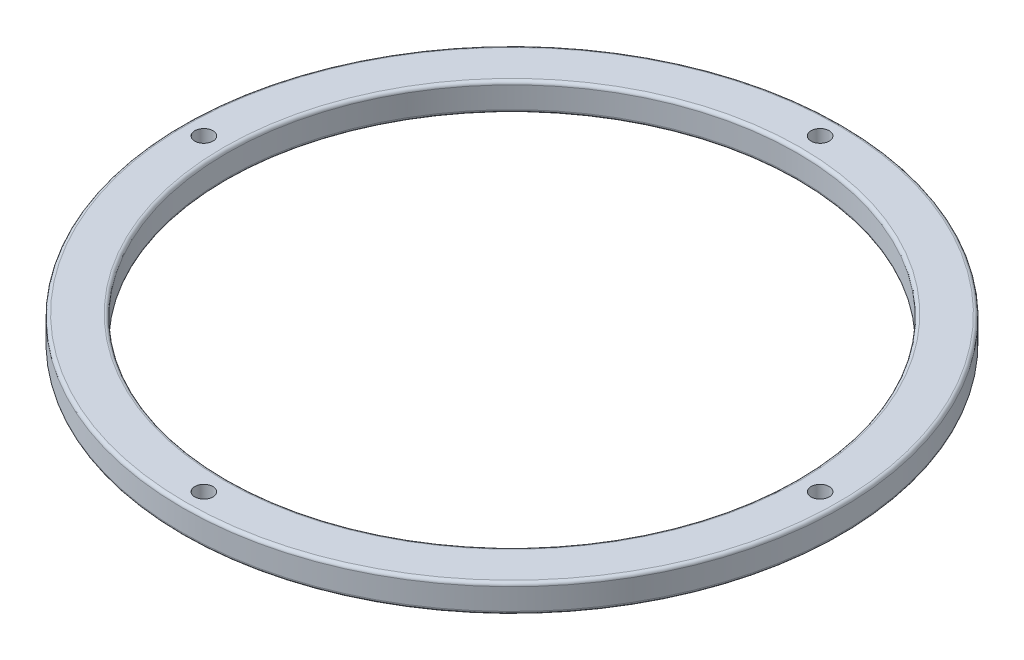
SolidWorks part; units mm, degrees
material "6061 Alloy"
ref_plane "Front Plane" through (0, 0, 0) normal (0, 0, 1) x (1, 0, 0)
ref_plane "Top Plane" through (0, 0, 0) normal (0, 1, 0) x (1, 0, 0)
ref_plane "Right Plane" through (0, 0, 0) normal (1, 0, 0) x (0, 0, -1)
sketch "Sketch1" plane through (0, 0, 0) normal (0, 1, 0) x (1, 0, 0)
  circle A0 centre (0, 0) radius 86.5
  circle A1 centre (0, 0) radius 100
  dimension "D1" = 173
  dimension "D2" = 200
extrude "Boss-Extrude1" add sketch "Sketch1" along normal blind 8.5
fillet "Fillet1" radius 1 4 edges at (0, 0, 86.5) (0, 0, 100) (0, 8.5, 86.5) (0, 8.5, 100)
sketch "Sketch2" plane through (0, 8.5, 0) normal (0, 1, 0) x (1, 0, 0)
  circle A0 centre (0, 0) radius 93.5 construction
  circle A4 centre (0, 93.5) radius 2.75
  circle A5 centre (93.5, 0) radius 2.75
  circle A6 centre (0, -93.5) radius 2.75
  circle A7 centre (-93.5, 0) radius 2.75
  point P5 (0, 93.5)
  point P6 (93.5, 0)
  point P7 (0, -93.5)
  point P8 (-93.5, 0)
  dimension "D1" = 187
  dimension "D2" = 5.5
  dimension "D3" = 5.5
  dimension "D4" = 5.5
  dimension "D5" = 5.5
extrude "Cut-Extrude1" cut sketch "Sketch2" against normal through all
